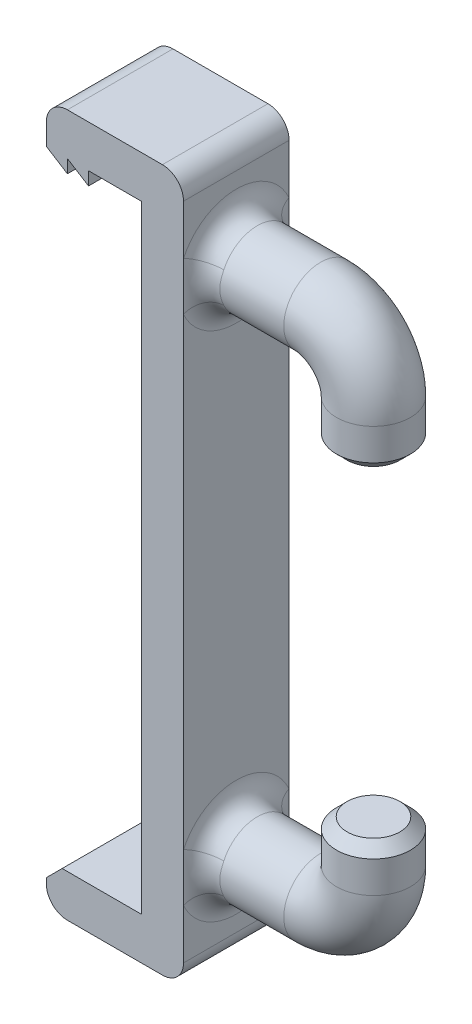
SolidWorks part; units mm, degrees
ref_plane "Front Plane" through (0, 0, 0) normal (0, 0, 1) x (1, 0, 0)
ref_plane "Top Plane" through (0, 0, 0) normal (0, 1, 0) x (1, 0, 0)
ref_plane "Right Plane" through (0, 0, 0) normal (1, 0, 0) x (0, 0, -1)
sketch "Sketch1" plane through (0, 0, 0) normal (0, 0, 1) x (1, 0, 0)
  line L17 (-13, 62.5) -> (-11, 61.25)
  line L19 (0, 2) -> (0, 64.5)
  line L20 (-2, 66.5) -> (-4, 66.5)
  line L21 (-4, 4) -> (-4, 62.5)
  line L22 (-4, 66.5) -> (-11, 66.5)
  line L24 (-4, 62.5) -> (-9, 62.5)
  line L25 (-13, 64.5) -> (-13, 62.5)
  line L26 (-2, 0) -> (-11, 0)
  line L28 (-4, 4) -> (-11.5, 4)
  line L29 (-13, 2) -> (-13, 2.5)
  line L30 (-11, 61.25) -> (-11, 62.5)
  line L31 (-11, 62.5) -> (-9, 61.25)
  line L32 (-9, 61.25) -> (-9, 62.5)
  line L33 (-11.5, 4) -> (-13, 2.5)
  arc A0 (-11, 0) -> (-13, 2) centre (-11, 2) cw
  arc A1 (-2, 0) -> (0, 2) centre (-2, 2) ccw
  arc A2 (0, 64.5) -> (-2, 66.5) centre (-2, 64.5) ccw
  arc A3 (-11, 66.5) -> (-13, 64.5) centre (-11, 64.5) ccw
  point P7 (-13, 4)
  point P16 (-13, 0)
  point P19 (0, 0)
  point P24 (-13, 66.5)
  dimension "D9" = 2
  dimension "D1" = 58.5
  dimension "D2" = 9
  dimension "D3" = 4
  dimension "D4" = 9
  dimension "D5" = 4
  dimension "D6" = 4
  dimension "D7" = 1.25
  dimension "D8" = 2
extrude "Boss-Extrude1" add sketch "Sketch1" along normal blind 10
sketch3d "3DSketch1"
  line L0 (0, 9, 5) -> (8, 9, 5)
  line L1 (0, 2, 5) -> (0, 64.5, 5) construction
  line L2 (0, 2, 10) -> (0, 2, 0) construction
  line L3 (0, 64.5, 10) -> (0, 64.5, 0) construction
  line L4 (13, 14, 5) -> (13, 18, 5)
  arc A0 (8, 9, 5) -> (13, 14, 5) centre (8, 14, 5) ccw
  point P10 (8, 14, 10)
  point P12 (0, 0, 0)
  point P13 (0, 0, 0)
  dimension "D6" = 5
  dimension "D1" = 7
  dimension "D3" = 13
  dimension "D5" = 4
sweep "Sweep1" add path "3DSketch1" circular profile diameter 7 parameters "D3"=7
fillet "Fillet1" radius 2 1 edges at (0, 9, 1.5)
ref_plane "Plane1" through (0, 33.25, 0) normal (0, -1, 0) x (-1, 0, 0)
chamfer "Chamfer1" distance 1 angle 45 1 edges at (13, 18, 1.5)
mirror "Mirror1" about plane through (0, 33.25, 0) normal (0, -1, 0) of "Chamfer1", "Sweep1", "Fillet1"
